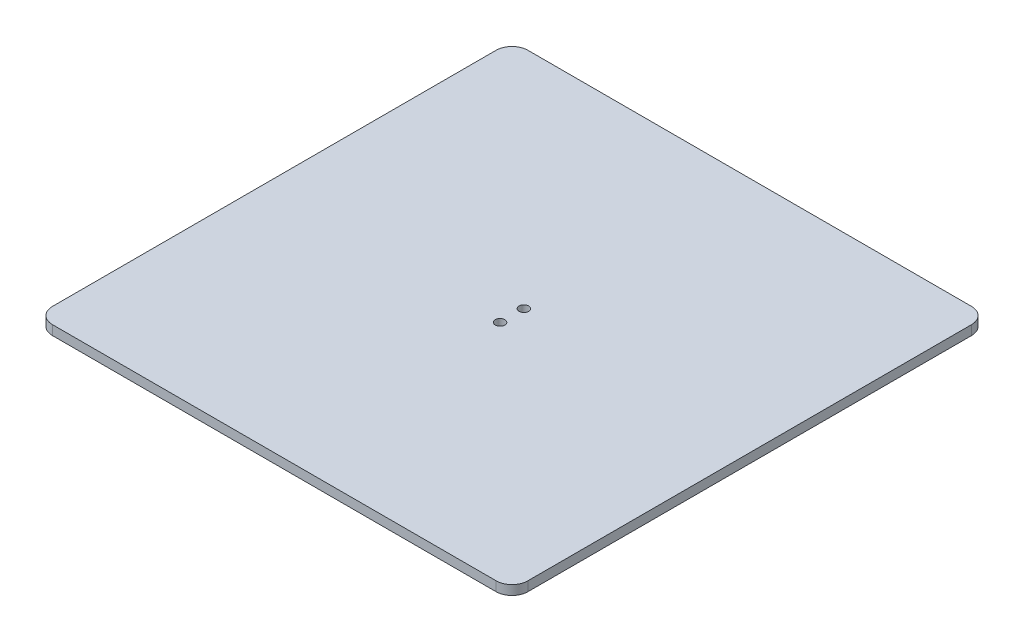
SolidWorks part; units mm, degrees
material "CA"
ref_plane "Front Plane" through (0, 0, 0) normal (0, 0, 1) x (1, 0, 0)
ref_plane "Top Plane" through (0, 0, 0) normal (0, 1, 0) x (1, 0, 0)
ref_plane "Right Plane" through (0, 0, 0) normal (1, 0, 0) x (0, 0, -1)
sketch "WeighingPlateform" plane through (0, 0, 0) normal (0, 1, 0) x (1, 0, 0)
  line L0 (-150, 0) -> (150, 0) construction
  line L1 (-150, 150) -> (150, 150)
  line L2 (-150, 150) -> (-150, -150)
  line L3 (-150, -150) -> (150, -150)
  line L4 (150, 150) -> (150, -150)
  circle A0 centre (0, 7.5) radius 3
  circle A1 centre (0, -7.5) radius 3
  point P4 (0, 150)
  point P5 (-150, 0)
  dimension "D3" = 6
  dimension "D4" = 6
  dimension "D6" = 7.5
  dimension "D1" = 300
  dimension "D2" = 300
  dimension "D5" = 7.5
extrude "Boss-Extrude1" add sketch "WeighingPlateform" along normal blind 6
fillet "Fillet1" radius 10 4 edges at (150, 3, -150) (-150, 3, -150) (-150, 3, 150) (150, 3, 150)
